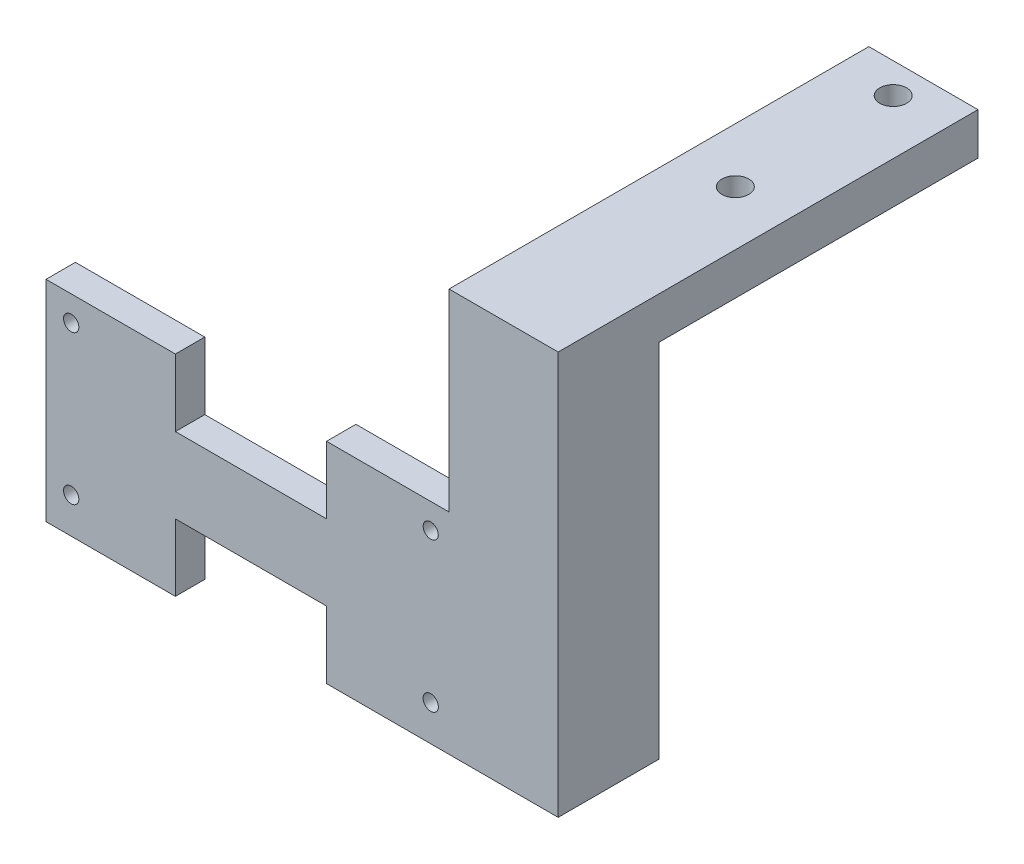
SolidWorks part; units mm, degrees
ref_plane "前视基准面" through (0, 0, 0) normal (0, 0, 1) x (1, 0, 0)
ref_plane "上视基准面" through (0, 0, 0) normal (0, 1, 0) x (1, 0, 0)
ref_plane "右视基准面" through (0, 0, 0) normal (1, 0, 0) x (0, 0, -1)
sketch "草图1" plane through (0, 0, 0) normal (0, 1, 0) x (1, 0, 0)
  line L1 (-6.5, 13) -> (6.5, 13)
  line L2 (-6.5, 13) -> (-6.5, -13)
  line L3 (-6.5, -13) -> (6.5, -13)
  line L4 (6.5, 13) -> (6.5, -13)
  line L5 (-6.5, 13) -> (6.5, -13) construction
  line L6 (-6.5, -13) -> (6.5, 13) construction
  point P0 (0, 0)
  dimension "D1" = 13
  dimension "D2" = 26
extrude "凸台-拉伸1" add sketch "草图1" along normal mid plane 5
sketch "草图2" plane through (0, 2.5, 0) normal (0, 1, 0) x (1, 0, 0)
  line L0 (-55, 0) -> (55, 0) construction
  circle A0 centre (0, 9.4) radius 1.6
  circle A1 centre (0, -9.4) radius 1.6
  dimension "D1" = 18.8
  dimension "D2" = 3.2
extrude "切除-拉伸1" cut sketch "草图2" against normal blind 13
sketch "草图3" plane through (0, 0, 13) normal (0, 0, 1) x (1, 0, 0)
  line L1 (-6.5, 2.5) -> (6.5, 2.5)
  line L2 (-6.5, 2.5) -> (-6.5, -2.5)
  line L3 (-6.5, -2.5) -> (6.5, -2.5)
  line L4 (6.5, 2.5) -> (6.5, -2.5)
extrude "凸台-拉伸2" add sketch "草图3" along normal blind 24
sketch "草图4" plane through (0, -2.5, 0) normal (0, -1, 0) x (1, 0, 0)
  line L0 (6.5, 37) -> (6.5, -13) construction
  line L1 (-6.5, 37) -> (6.5, 37)
  line L2 (-6.5, 37) -> (-6.5, 25)
  line L3 (-6.5, 25) -> (6.5, 25)
  line L4 (6.5, 37) -> (6.5, 25)
  dimension "D1" = 12
extrude "凸台-拉伸3" add sketch "草图4" along normal blind 43
sketch "草图5" plane through (-6.5, 0, 0) normal (-1, 0, 0) x (0, 0, 1)
  line L6 (37, -45.5) -> (33.5, -45.5)
  line L7 (37, -45.5) -> (37, -20.5)
  line L8 (37, -20.5) -> (33.5, -20.5)
  line L9 (33.5, -45.5) -> (33.5, -20.5)
  dimension "D1" = 25
  dimension "D2" = 3.5
extrude "凸台-拉伸4" add sketch "草图5" along normal blind 48
sketch "草图6" plane through (0, 0, 37) normal (0, 0, 1) x (1, 0, 0)
  line L0 (-54.5, -45.5) -> (-54.5, -20.5) construction
  line L1 (-54.5, -20.5) -> (-6.5, -20.5) construction
  circle A0 centre (-51.5, -23.5) radius 0.91
  circle A1 centre (-8.68, -23.5) radius 0.9
  circle A2 centre (-51.5, -41.24) radius 0.91
  circle A3 centre (-8.68, -41.24) radius 0.91
  dimension "D1" = 42.82
  dimension "D2" = 1.82
  dimension "D3" = 1.8
  dimension "D4" = 3
  dimension "D5" = 3
  dimension "D6" = 1.82
  dimension "D7" = 1.82
  dimension "D8" = 17.74
extrude "切除-拉伸2" cut sketch "草图6" against normal blind 16
sketch "草图7" plane through (0, 0, 37) normal (0, 0, 1) x (1, 0, 0)
  line L0 (-51.5, -23.5) -> (-8.68, -23.5) construction
  line L1 (-54.5, -20.5) -> (-6.5, -20.5) construction
  line L2 (-39.09, -28.5) -> (-21.09, -28.5)
  line L3 (-39.09, -28.5) -> (-39.09, -20.5)
  line L4 (-39.09, -20.5) -> (-21.09, -20.5)
  line L5 (-21.09, -28.5) -> (-21.09, -20.5)
  line L6 (-39.09, -28.5) -> (-21.09, -20.5) construction
  line L7 (-39.09, -20.5) -> (-21.09, -28.5) construction
  line L8 (-51.5, -23.5) -> (-51.5, -41.24) construction
  line L9 (-54.5, -20.5) -> (-54.5, -45.5) construction
  line L10 (6.5, -45.5) -> (-54.5, -45.5) construction
  line L11 (-54.5, -45.5) -> (-54.5, -20.5) construction
  line L12 (-54.5, -33) -> (6.5, -33) construction
  line L13 (6.5, -45.5) -> (6.5, 2.5) construction
  line L14 (-39.09, -45.5) -> (-21.09, -37.5) construction
  line L15 (-39.09, -37.5) -> (-21.09, -45.5) construction
  line L16 (-21.09, -37.5) -> (-21.09, -45.5)
  line L17 (-39.09, -45.5) -> (-21.09, -45.5)
  line L18 (-39.09, -37.5) -> (-39.09, -45.5)
  line L19 (-39.09, -37.5) -> (-21.09, -37.5)
  point P4 (-30.09, -24.5)
  point P24 (0, 0)
  point P29 (0, 0)
  point P30 (0, 0)
  point P31 (-30.09, -41.5)
  dimension "D1" = 8
extrude "切除-拉伸3" cut sketch "草图7" against normal blind 16
